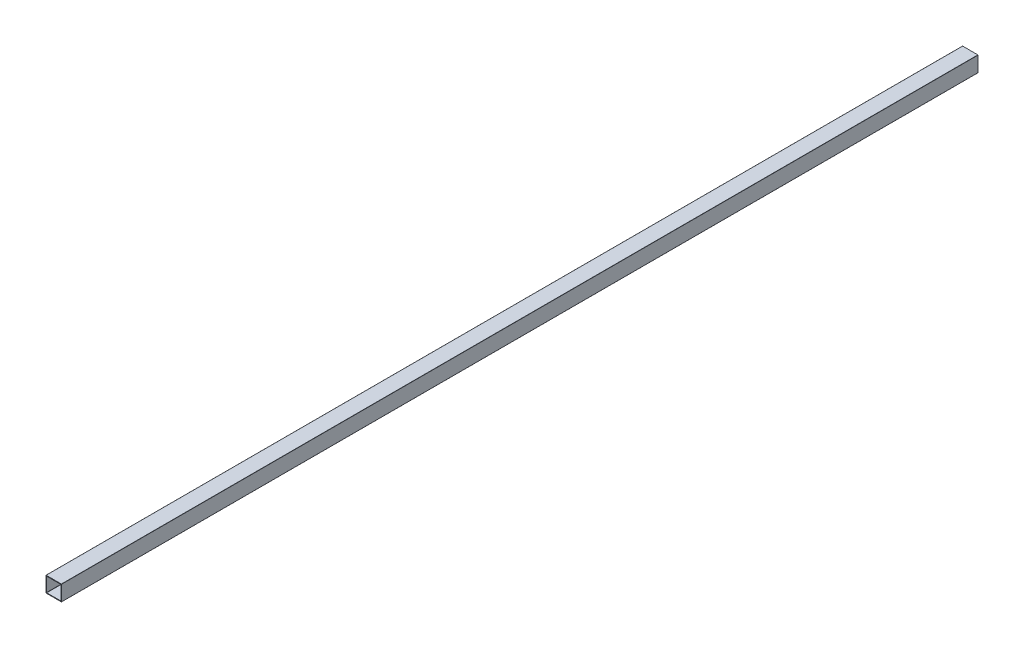
SolidWorks part; units mm, degrees
material "AISI 1035 Acero (SS)"
ref_plane "Alzado" through (0, 0, 0) normal (0, 0, 1) x (1, 0, 0)
ref_plane "Planta" through (0, 0, 0) normal (0, 1, 0) x (1, 0, 0)
ref_plane "Vista lateral" through (0, 0, 0) normal (1, 0, 0) x (0, 0, -1)
sketch "Croquis1" plane through (0, 0, 0) normal (0, 0, 1) x (1, 0, 0)
  line L0 (-47, -47) -> (-47, 47)
  line L1 (-50.8, -50.8) -> (50.8, -50.8)
  line L2 (-50.8, -50.8) -> (-50.8, 50.8)
  line L3 (-50.8, 50.8) -> (50.8, 50.8)
  line L4 (50.8, -50.8) -> (50.8, 50.8)
  line L5 (-50.8, -50.8) -> (50.8, 50.8) construction
  line L6 (-50.8, 50.8) -> (50.8, -50.8) construction
  line L7 (-47, 47) -> (47, 47)
  line L8 (47, -47) -> (47, 47)
  line L9 (-47, -47) -> (47, -47)
  point P0 (0, 0)
  dimension "D2" = 101.6
  dimension "D3" = 3.8
extrude "Saliente-Extruir1" add sketch "Croquis1" against normal blind 6000
fillet "Redondeo1" radius 1 8 edges at (-47, 47, -3000) (47, 47, -3000) (47, -47, -3000) (-50.8, -50.8, -3000) (-50.8, 50.8, -3000) (-47, -47, -3000) (50.8, -50.8, -3000) (50.8, 50.8, -3000)
